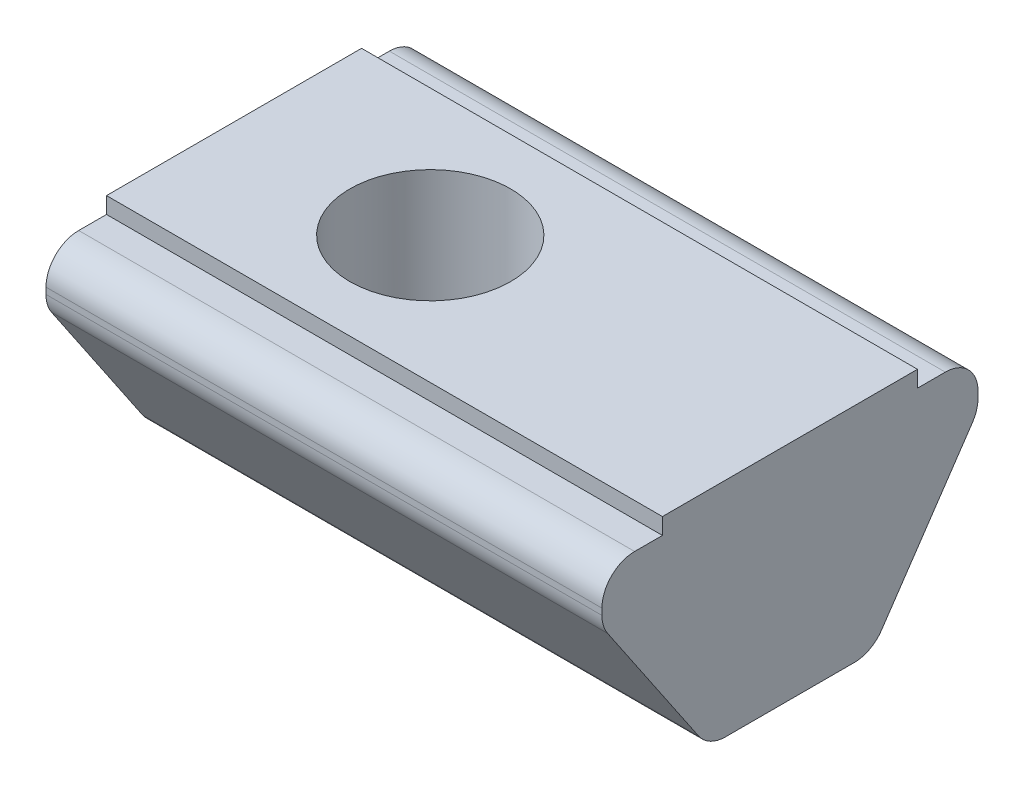
SolidWorks part; units mm, degrees
ref_plane "Front Plane" through (0, 0, 0) normal (0, 0, 1) x (1, 0, 0)
ref_plane "Top Plane" through (0, 0, 0) normal (0, 1, 0) x (1, 0, 0)
ref_plane "Right Plane" through (0, 0, 0) normal (1, 0, 0) x (0, 0, -1)
ref_plane "Plane1" through (-6, 0, 0) normal (1, 0, 0) x (0, 0, -1)
ref_plane "Plane2" through (7.5, 0, 0) normal (1, 0, 0) x (0, 0, -1)
ref_plane "Plane3" through (-3.1, 0, 0) normal (1, 0, 0) x (0, 0, -1)
sketch "Axis_Line_X" plane through (0, 0, 0) normal (0, 1, 0) x (1, 0, 0)
  line L0 (0, 0) -> (50, 0)
  dimension "FIX_2" = 50
sketch "Axis_Line_Z" plane through (0, 0, 0) normal (0, 1, 0) x (1, 0, 0)
  line L0 (0, 0) -> (0, -50)
  dimension "FIX_3" = 50
sketch "Sketch1" plane through (-6, 0, 0) normal (1, 0, 0) x (0, 0, -1)
  line L0 (3.9, 0) -> (-3.9, 0)
  line L1 (-3.9, 0) -> (-3.9, -0.5)
  line L2 (-3.9, -0.5) -> (-5.75, -0.5)
  line L3 (-5.75, -0.5) -> (-5.75, -2)
  line L4 (-5.75, -2) -> (-2.5, -6.8)
  line L5 (-2.5, -6.8) -> (2.5, -6.8)
  line L6 (2.5, -6.8) -> (5.75, -2)
  line L7 (5.75, -2) -> (5.75, -0.5)
  line L8 (5.75, -0.5) -> (3.9, -0.5)
  line L9 (3.9, -0.5) -> (3.9, 0)
  line L10 (0, 0) -> (0, -6.8) construction
  point P15 (-5.75, -2)
  point P18 (-2.5, -6.8)
  point P24 (5.75, -2)
  dimension "FIX_8" = 6.3
  dimension "FIX_9" = 1.5
  dimension "FIX_4" = 11.5
  dimension "FIX_6" = 7.8
  dimension "FIX_5" = 6.8
  dimension "FIX_7" = 5
extrude "Boss-Extrude1" add sketch "Sketch1" along normal blind 17
fillet "Fillet1" radius 1 6 edges at (2.5, -0.5, 5.75) (2.5, -2, 5.75) (2.5, -6.8, 2.5) (2.5, -6.8, -2.5) (2.5, -2, -5.75) (2.5, -0.5, -5.75)
sketch "Sketch2" plane through (7.5, 0, 0) normal (1, 0, 0) x (0, 0, -1)
  line L0 (0, 1.6655) -> (0, -9.505) construction
  line L2 (0, -6.6) -> (2.35, -6.6)
  line L3 (0, -6.6) -> (0, -6.8)
  line L4 (0, -6.8) -> (2.35, -6.8)
  line L5 (2.35, -6.6) -> (2.35, -6.8)
  dimension "FIX_13" = 0.2
  dimension "FIX_12" = 2.35
  dimension "FIX_11" = 6.8
revolve "Cut-Revolve1" cut sketch "Sketch2" angle 360 about L0
sketch "Sketch3" plane through (7.5, 0, 0) normal (1, 0, 0) x (0, 0, -1)
  line L0 (0, 0) -> (0, -7.8) construction
  line L1 (1.99, -6.6) -> (0, -6.6) construction
  line L2 (1.99, -7.8) -> (0, -7.8) construction
  line L3 (1.99, -6.6) -> (0, -6.6)
  line L4 (0, -6.6) -> (0, -7.8)
  arc A0 (0, -7.8) -> (1.99, -6.6) centre (0, -5.55) ccw
  dimension "FIX_17" = 4.5
  dimension "FIX_15" = 7.8
  dimension "FIX_16" = 6.6
revolve "Revolve1" add sketch "Sketch3" angle 360 about L0
hole_wizard "Tapped Hole1" positions "Sketch5" profile "Sketch4" tap size "M6x1.0" standard "JIS" end condition through all
sketch "Sketch5" plane through (0, 0, 0) normal (0, 1, 0) x (1, 0, 0)
  point P0 (0, 0)
cosmetic thread "Thread1" parameters "NFIX_1"=6
sketch "Sketch4" plane through (0, 0, 0) normal (1, 0, 0) x (0, 0, 1)
  line L0 (0, 0) -> (0, 7.8)
  line L1 (0, 7.8) -> (2.4585, 7.8)
  line L2 (2.4585, 7.8) -> (2.4585, 0)
  line L5 (2.4585, 0) -> (0, 0)
  line L11 (0, 0) -> (0, 7.8) construction
  dimension "Thru Tap Drill Dia." = 4.917
  dimension "Thru Tap Drill Depth" = 7.8
sketch "Sketch6" [suppressed] plane through (-3.1, 0, 0) normal (1, 0, 0) x (0, 0, -1)
  line L0 (4.9, -0.4) -> (4.9, -0.5)
  line L1 (4.9, -0.5) -> (5, -0.5)
  line L2 (4.9, -0.4) -> (4.9, -0.5) construction
  arc A0 (5, -0.5) -> (4.9, -0.4) centre (4.9, -0.5) ccw
  dimension "FIX_21" = 0.1
  dimension "FIX_19" = 4.9
  dimension "FIX_20" = 0.5
revolve "Revolve2" [suppressed] add sketch "Sketch6" angle 360 about L2
pattern_linear "LPattern1" [suppressed]
equation "\"SHNTP6\" = if ( \"L1\" = 6 , \"suppressed\" , \"unsuppressed\" )"
